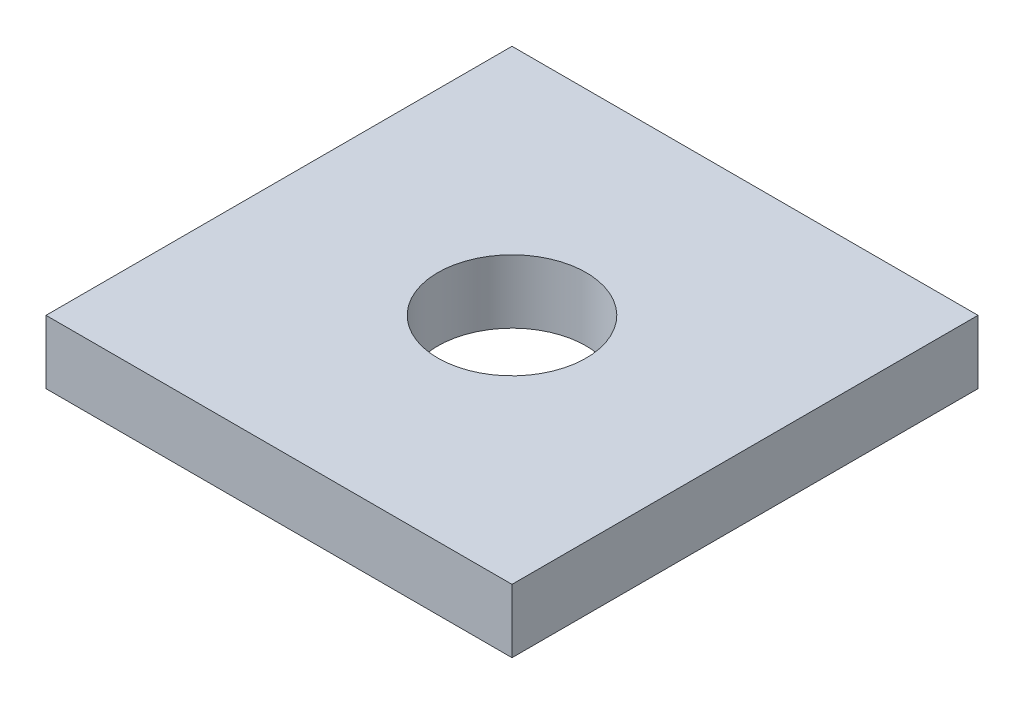
SolidWorks part; units mm, degrees
ref_plane "Front Plane" through (0, 0, 0) normal (0, 0, 1) x (1, 0, 0)
ref_plane "Top Plane" through (0, 0, 0) normal (0, 1, 0) x (1, 0, 0)
ref_plane "Right Plane" through (0, 0, 0) normal (1, 0, 0) x (0, 0, -1)
sketch "Sketch1" plane through (0, 0, 0) normal (0, 1, 0) x (1, 0, 0)
  line L0 (0, 6.6126) -> (0, -7.0178) construction
  line L1 (-7.9106, 0) -> (8.5765, 0) construction
  line L3 (-11, -11) -> (11, -11)
  line L4 (-11, -11) -> (-11, 11)
  line L5 (-11, 11) -> (11, 11)
  line L6 (11, -11) -> (11, 11)
  line L7 (-11, -11) -> (11, 11) construction
  line L8 (-11, 11) -> (11, -11) construction
  circle A0 centre (0, 0) radius 3.5
  point P5 (0, 0)
  dimension "D1" = 7
  dimension "D2" = 11
  dimension "D3" = 11
extrude "Boss-Extrude1" add sketch "Sketch1" along normal blind 3
